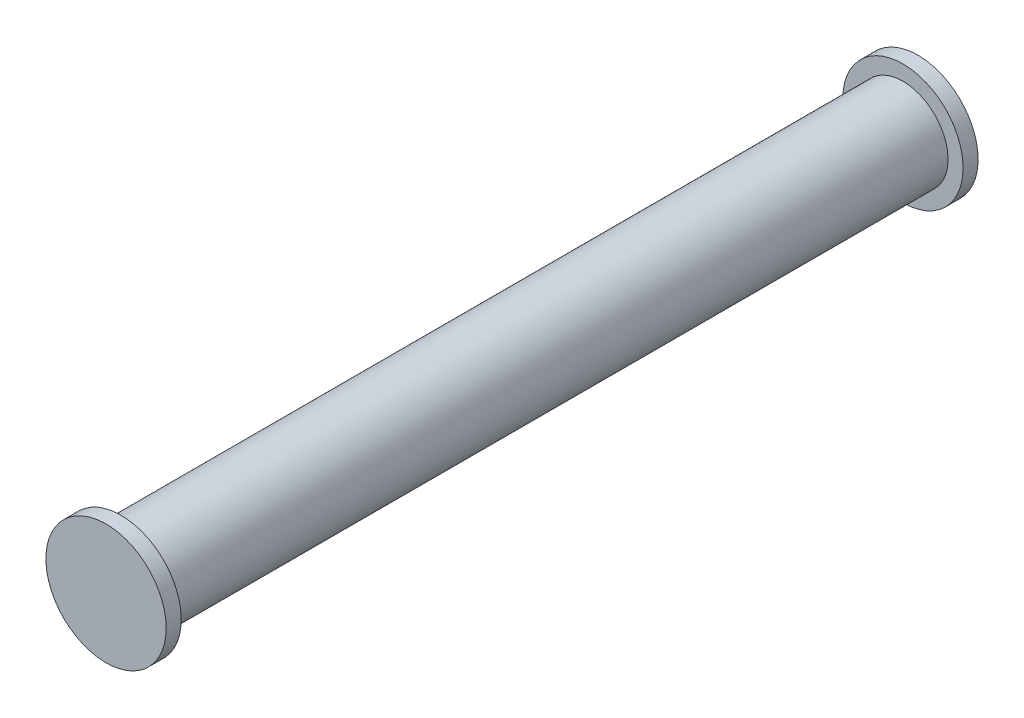
SolidWorks part; units mm, degrees
ref_plane "Plan de face" through (0, 0, 0) normal (0, 0, 1) x (1, 0, 0)
ref_plane "Plan de dessus" through (0, 0, 0) normal (0, 1, 0) x (1, 0, 0)
ref_plane "Plan de droite" through (0, 0, 0) normal (1, 0, 0) x (0, 0, -1)
sketch "Esquisse1" plane through (0, 0, 0) normal (0, 0, 1) x (1, 0, 0)
  circle A0 centre (0, 0) radius 1.5
  dimension "D1" = 3
extrude "Boss.-Extru.1" add sketch "Esquisse1" along normal blind 26
sketch "Esquisse2" plane through (0, 0, 26) normal (0, 0, 1) x (1, 0, 0)
  circle A2 centre (0, 0) radius 2
  circle A3 centre (0, 0) radius 2
  dimension "D1" = 0.5
extrude "Boss.-Extru.2" add sketch "Esquisse2" along normal blind 0.5
sketch "Esquisse4" plane through (0, 0, 0) normal (0, 0, -1) x (-1, 0, 0)
  circle A2 centre (0, 0) radius 2
  circle A3 centre (0, 0) radius 2
  dimension "D1" = 0.5
extrude "Boss.-Extru.4" add sketch "Esquisse4" along normal blind 0.5
